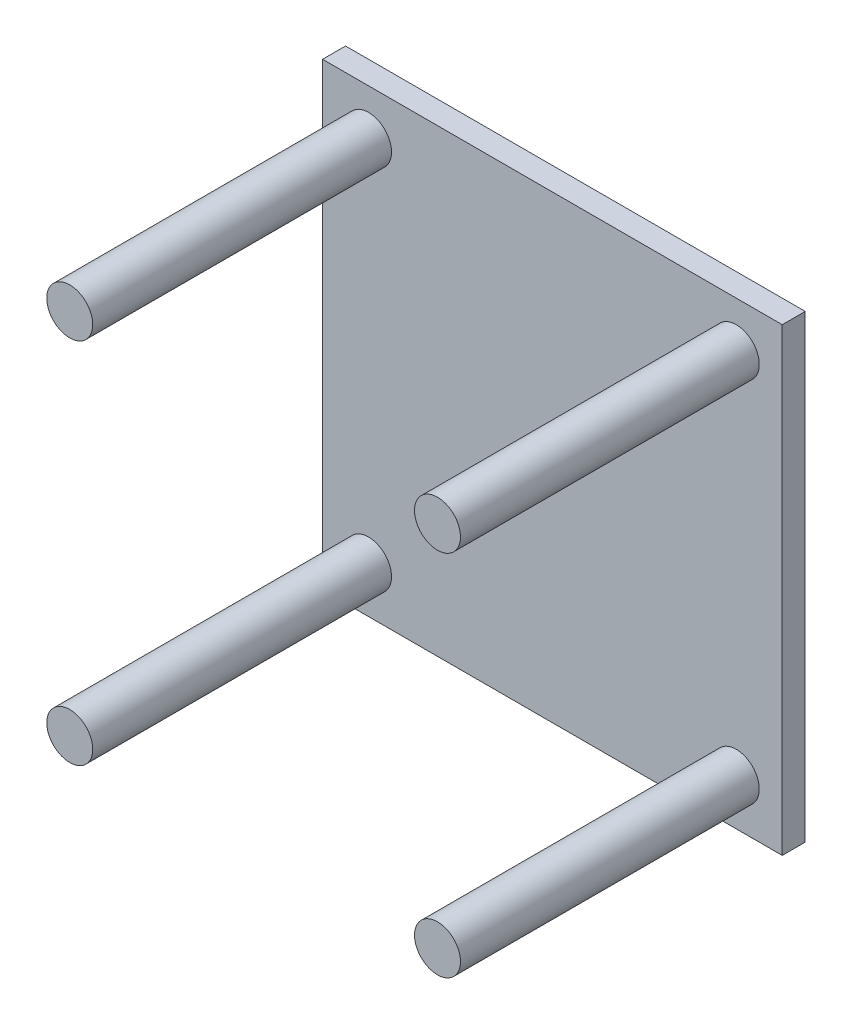
SolidWorks part; units mm, degrees
ref_plane "前视基准面" through (0, 0, 0) normal (0, 0, 1) x (1, 0, 0)
ref_plane "上视基准面" through (0, 0, 0) normal (0, 1, 0) x (1, 0, 0)
ref_plane "右视基准面" through (0, 0, 0) normal (1, 0, 0) x (0, 0, -1)
other "Configuration Table"
sketch "草图1" plane through (0, 0, 0) normal (0, 0, 1) x (1, 0, 0)
  line L1 (-500, -500) -> (500, -500)
  line L2 (-500, -500) -> (-500, 500)
  line L3 (-500, 500) -> (500, 500)
  line L4 (500, -500) -> (500, 500)
  line L5 (-500, -500) -> (500, 500) construction
  line L6 (-500, 500) -> (500, -500) construction
extrude "凸台-拉伸1" add sketch "草图1" along normal blind 50
sketch "草图2" plane through (0, 0, 0) normal (0, 0, 1) x (1, 0, 0)
  circle A0 centre (400, 400) radius 50
extrude "凸台-拉伸2" add sketch "草图2" along normal blind 700
sketch "草图3" plane through (0, 0, 0) normal (0, 0, 1) x (1, 0, 0)
  circle A0 centre (-400, 400) radius 50
extrude "凸台-拉伸3" add sketch "草图3" along normal blind 700
sketch "草图4" plane through (0, 0, 0) normal (0, 0, 1) x (1, 0, 0)
  circle A0 centre (400, -400) radius 50
extrude "凸台-拉伸4" add sketch "草图4" along normal blind 700
sketch "草图5" plane through (0, 0, 0) normal (0, 0, 1) x (1, 0, 0)
  circle A0 centre (-400, -400) radius 50
extrude "凸台-拉伸5" add sketch "草图5" along normal blind 700
